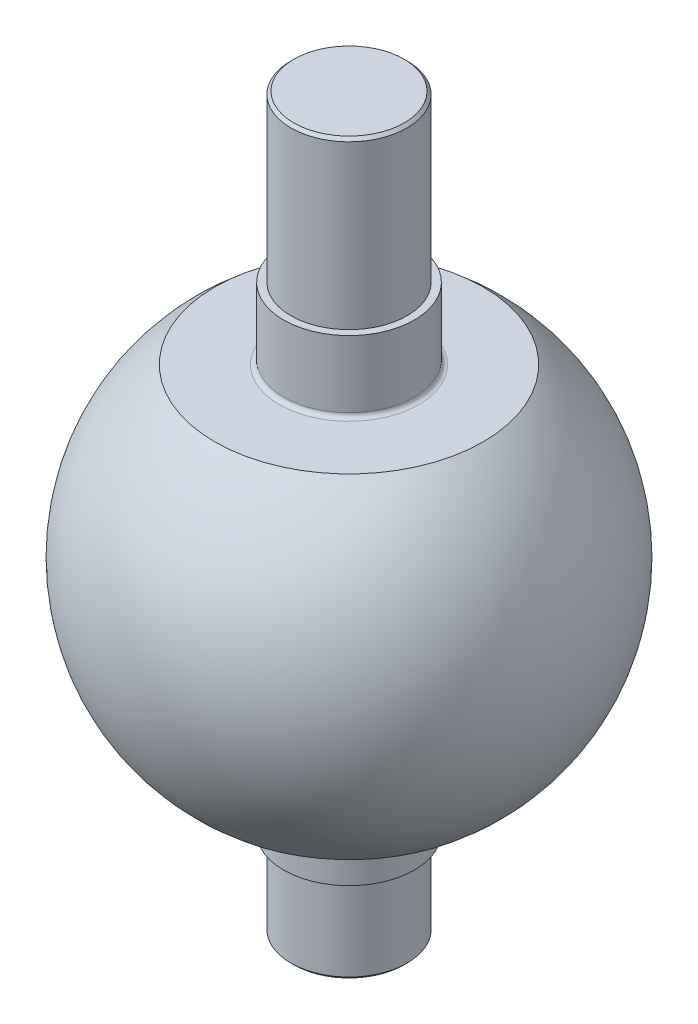
SolidWorks part; units mm, degrees
material "Сплав 3М ОСТ 1-92077-91"
ref_plane "Спереди" through (0, 0, 0) normal (0, 0, 1) x (1, 0, 0)
ref_plane "Сверху" through (0, 0, 0) normal (0, 1, 0) x (1, 0, 0)
ref_plane "Справа" through (0, 0, 0) normal (1, 0, 0) x (0, 0, -1)
sketch "Эскиз1" plane through (0, 0, 0) normal (0, 0, 1) x (1, 0, 0)
  line L0 (0, 332.3833) -> (0, -282.3933) construction
  line L2 (-92.3648, 115) -> (-48, 115)
  line L3 (-45, 118) -> (-45, 164)
  line L5 (-45, 164) -> (-40, 164)
  line L6 (-40, 164) -> (-40, 276)
  line L7 (-38, 278) -> (0, 278)
  line L8 (0, 278) -> (0, -224)
  line L9 (0, -224) -> (-38, -224)
  line L10 (-40, -222) -> (-40, -164)
  line L11 (-40, -164) -> (-45, -164)
  line L13 (-45, -164) -> (-45, -118)
  line L14 (-48, -115) -> (-92.3648, -115)
  line L15 (-40, 276) -> (-38, 278)
  line L16 (-38, -224) -> (-40, -222)
  arc A1 (-92.3648, 115) -> (-92.3648, -115) centre (0, 0) ccw
  arc A3 (-48, 115) -> (-45, 118) centre (-48, 118) ccw
  arc A4 (-45, -118) -> (-48, -115) centre (-48, -118) ccw
  point P14 (-40, 278)
  point P17 (-40, -224)
  dimension "D21" = 3
  dimension "D9" = 295
  dimension "D3" = 230
  dimension "D4" = 80
  dimension "D5" = 2
  dimension "D6" = 45
  dimension "D7" = 90
  dimension "D8" = 80
  dimension "D11" = 90
  dimension "D12" = 502
  dimension "D13" = 163
  dimension "D14" = 114
  dimension "D15" = 60
  dimension "D16" = 2
  dimension "D17" = 45
revolve "Повернуть1" add sketch "Эскиз1" angle 360 about L0
sketch "Эскиз2" plane through (0, 0, 0) normal (0, 1, 0) x (1, 0, 0)
  line L0 (0, 169.6465) -> (0, -175.1647) construction
  line L1 (0, 147.5) -> (-98.2662, 147.5)
  line L2 (-98.2662, 147.5) -> (-98.2662, 110)
  line L3 (-98.2662, 110) -> (-87.5, 110)
  line L4 (-87.5, 110) -> (-87.5, 100)
  line L5 (-87.5, 100) -> (-92.5, 100)
  line L6 (-92.5, 100) -> (-92.5, -110)
  line L7 (-92.5, -110) -> (-98.2662, -110)
  line L8 (-98.2662, -110) -> (-98.2662, -147.5)
  line L9 (-98.2662, -147.5) -> (0, -147.5)
  line L10 (0, -147.5) -> (0, 147.5)
  circle A0 centre (0, 0) radius 147.5 construction
  dimension "D1" = 220
  dimension "D2" = 10
  dimension "D3" = 110
  dimension "D4" = 175
  dimension "D5" = 185
